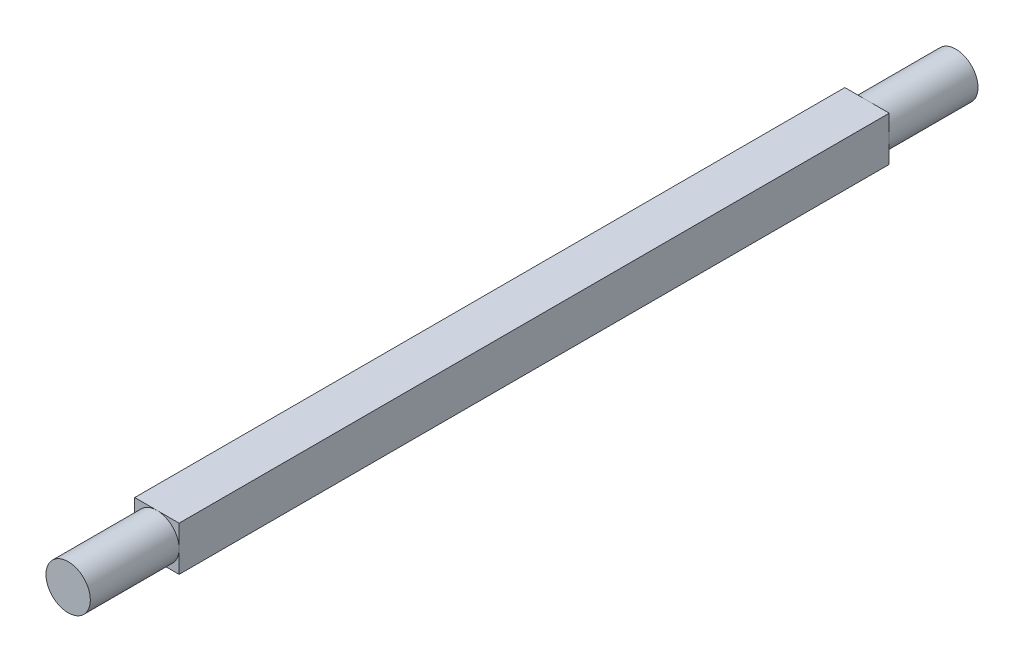
SolidWorks part; units mm, degrees
ref_plane "Front Plane" through (0, 0, 0) normal (0, 0, 1) x (1, 0, 0)
ref_plane "Top Plane" through (0, 0, 0) normal (0, 1, 0) x (1, 0, 0)
ref_plane "Right Plane" through (0, 0, 0) normal (1, 0, 0) x (0, 0, -1)
sketch "Sketch1" plane through (0, 0, 0) normal (0, 0, 1) x (1, 0, 0)
  line L1 (-25, 25) -> (25, 25)
  line L2 (-25, 25) -> (-25, -25)
  line L3 (-25, -25) -> (25, -25)
  line L4 (25, 25) -> (25, -25)
  line L5 (-25, 25) -> (25, -25) construction
  line L6 (-25, -25) -> (25, 25) construction
  point P0 (0, 0)
  dimension "D1" = 50
  dimension "D2" = 50
extrude "Boss-Extrude1" add sketch "Sketch1" along normal mid plane 800
sketch "Sketch2" plane through (0, 0, 400) normal (0, 0, 1) x (1, 0, 0)
  circle A0 centre (0, 0) radius 25
  dimension "D1" = 50
extrude "Boss-Extrude2" add sketch "Sketch2" along normal blind 100
mirror "Mirror1" about plane through (0, 0, 0) normal (0, 0, 1) of "Boss-Extrude2"
